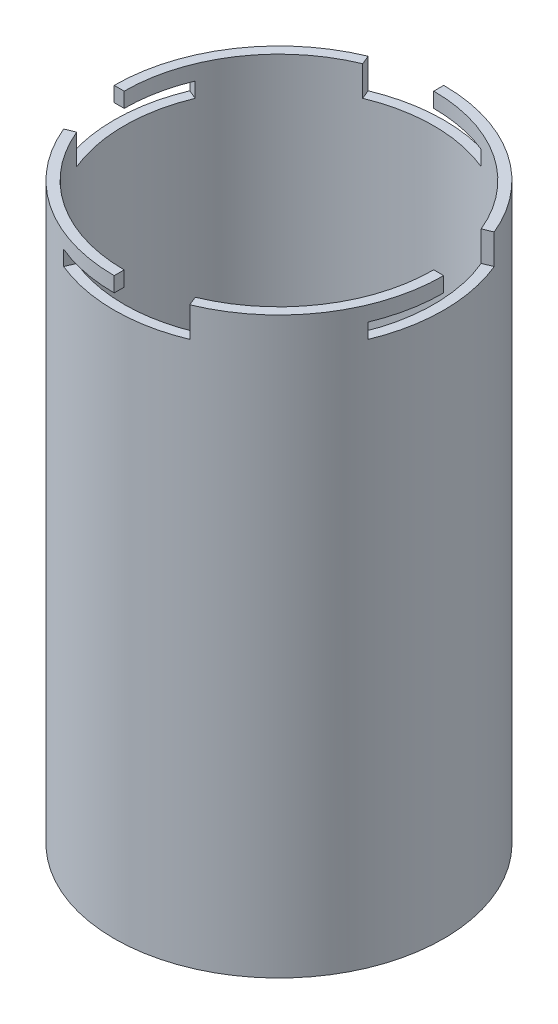
SolidWorks part; units mm, degrees
ref_plane "Front Plane" through (0, 0, 0) normal (0, 0, 1) x (1, 0, 0)
ref_plane "Top Plane" through (0, 0, 0) normal (0, 1, 0) x (1, 0, 0)
ref_plane "Right Plane" through (0, 0, 0) normal (1, 0, 0) x (0, 0, -1)
sketch "Sketch1" plane through (0, 0, 0) normal (0, 1, 0) x (1, 0, 0)
  circle A0 centre (0, 0) radius 33
extrude "Boss-Extrude1" add sketch "Sketch1" along normal blind 109
sketch "Sketch2" plane through (0, 109, 0) normal (0, 1, 0) x (1, 0, 0)
  line L1 (28.6403, -11.8632) -> (30.488, -12.6286)
  line L4 (28.6403, 11.8632) -> (30.488, 12.6286)
  line L5 (11.8632, 28.6403) -> (12.6286, 30.488)
  line L6 (11.8632, -28.6403) -> (12.6286, -30.488)
  line L16 (-30.488, -12.6286) -> (-28.6403, -11.8632)
  line L17 (-12.6286, -30.488) -> (-11.8632, -28.6403)
  line L18 (-12.6286, 30.488) -> (-11.8632, 28.6403)
  line L19 (-30.488, 12.6286) -> (-28.6403, 11.8632)
  circle A0 centre (0, 0) radius 33
  circle A2 centre (0, 0) radius 31
  circle M7 centre (0, 0) radius 33
extrude "Boss-Extrude3" add sketch "Sketch2" along normal blind 3 contours A2 | A2 L18 L19 M7 | A2 L4 L5 M7 | A2 L6 L1 M7 | A2 L16 L17 M7
sketch "Sketch3" plane through (0, 112, 0) normal (0, 1, 0) x (1, 0, 0)
  line L2 (-33, 0) -> (-31, 0)
  line L5 (0, 33) -> (0, 31)
  line L6 (31, 0) -> (33, 0)
  line L7 (0, -33) -> (0, -31)
  arc A0 (12.6286, -30.488) -> (33, 0) centre (0, 0) ccw
  arc A1 (-30.488, -12.6286) -> (0, -33) centre (0, 0) ccw
  arc A2 (30.488, 12.6286) -> (0, 33) centre (0, 0) ccw
  arc A3 (-12.6286, 30.488) -> (-33, 0) centre (0, 0) ccw
  arc A4 (-28.6403, 11.8632) -> (-28.6403, -11.8632) centre (0, 0) ccw construction
  arc A5 (11.8632, 28.6403) -> (-11.8632, 28.6403) centre (0, 0) ccw construction
  arc A6 (28.6403, -11.8632) -> (28.6403, 11.8632) centre (0, 0) ccw construction
  arc A7 (-11.8632, -28.6403) -> (11.8632, -28.6403) centre (0, 0) ccw construction
  arc A8 (0, -31) -> (0, 31) centre (0, 0) ccw
  circle A9 centre (0, 0) radius 31
extrude "Boss-Extrude4" add sketch "Sketch3" along normal blind 3
sketch "Sketch4" plane through (0, 115, 0) normal (0, 1, 0) x (1, 0, 0)
  circle A0 centre (0, 0) radius 31
extrude "Cut-Extrude1" cut sketch "Sketch4" against normal blind 115
